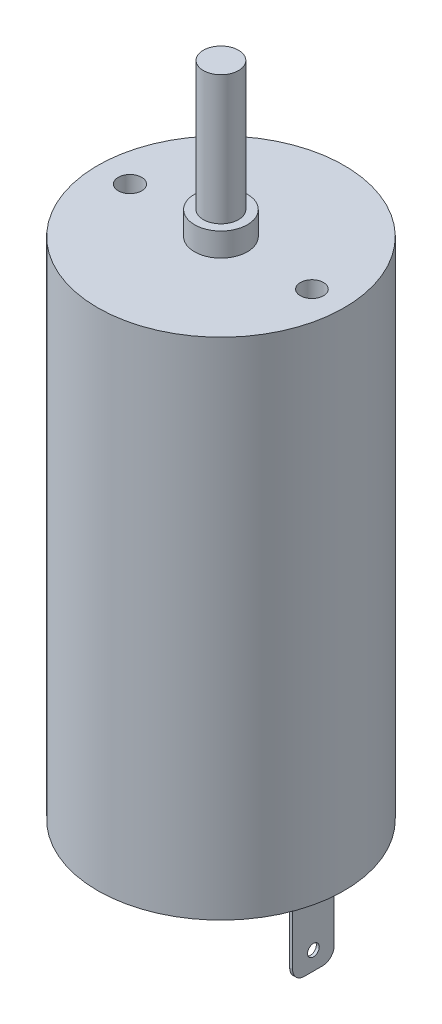
SolidWorks part; units mm, degrees
ref_plane "Front Plane" through (0, 0, 0) normal (0, 0, 1) x (1, 0, 0)
ref_plane "Top Plane" through (0, 0, 0) normal (0, 1, 0) x (1, 0, 0)
ref_plane "Right Plane" through (0, 0, 0) normal (1, 0, 0) x (0, 0, -1)
sketch "Sketch1" plane through (0, 0, 0) normal (0, 1, 0) x (1, 0, 0)
  circle A0 centre (0, 0) radius 10.5
extrude "Boss-Extrude1" add sketch "Sketch1" along normal blind 43
sketch "Sketch2" plane through (0, 43, 0) normal (0, 1, 0) x (1, 0, 0)
  circle A0 centre (0, 0) radius 1.5
extrude "Boss-Extrude2" add sketch "Sketch2" along normal blind 13
sketch "Sketch3" plane through (0, 43, 0) normal (0, 1, 0) x (1, 0, 0)
  circle A0 centre (0, 0) radius 2.25
extrude "Boss-Extrude3" add sketch "Sketch3" along normal blind 2
sketch "Sketch4" plane through (0, 43, 0) normal (0, 1, 0) x (1, 0, 0)
  line L0 (0, 0) -> (10.5, 0) construction
  line L1 (0, 0) -> (-10.5, 0) construction
  circle A0 centre (7.75, 0) radius 0.9839
  circle A1 centre (0, 0) radius 10.5 construction
  circle A2 centre (-7.75, 0) radius 1
  dimension "D1" = 2.75
  dimension "D2" = 2.75
extrude "Cut-Extrude1" cut sketch "Sketch4" against normal blind 7.5
sketch "Sketch5" plane through (0, 0, 0) normal (0, -1, 0) x (1, 0, 0)
  line L0 (0, 0) -> (10.5, 0) construction
  line L1 (10.5, 0) -> (-10.5, 0) construction
  line L3 (7.875, -2) -> (7.625, -2)
  line L4 (7.875, -2) -> (7.875, 2)
  line L5 (7.875, 2) -> (7.625, 2)
  line L6 (7.625, -2) -> (7.625, 2)
  line L7 (7.875, -2) -> (7.625, 2) construction
  line L8 (7.875, 2) -> (7.625, -2) construction
  line L9 (-7.625, -2) -> (-7.875, -2)
  line L10 (-7.625, -2) -> (-7.625, 2)
  line L11 (-7.625, 2) -> (-7.875, 2)
  line L12 (-7.875, -2) -> (-7.875, 2)
  line L13 (-7.625, -2) -> (-7.875, 2) construction
  line L14 (-7.625, 2) -> (-7.875, -2) construction
  circle A0 centre (0, 0) radius 10.5 construction
  point P6 (7.75, 0)
  point P12 (-7.75, 0)
  dimension "D1" = 0.25
  dimension "D2" = 4
  dimension "D3" = 2.75
  dimension "D4" = 0.25
  dimension "D5" = 4
  dimension "D6" = 2.75
extrude "Boss-Extrude4" add sketch "Sketch5" along normal blind 1.25
sketch "Sketch6" plane through (0, -1.25, 0) normal (0, -1, 0) x (1, 0, 0)
  line L0 (-7.625, -2) -> (-7.625, 2) construction
  line L1 (-7.625, 1.775) -> (-7.875, 1.775)
  line L2 (-7.625, 1.775) -> (-7.625, -1.775)
  line L3 (-7.625, -1.775) -> (-7.875, -1.775)
  line L4 (-7.875, 1.775) -> (-7.875, -1.775)
  line L5 (-7.875, 2) -> (-7.875, -2) construction
  line L6 (-7.625, 2) -> (-7.875, 2) construction
  line L7 (-7.875, -2) -> (-7.625, -2) construction
  dimension "D1" = 0.225
  dimension "D2" = 0.225
extrude "Boss-Extrude5" add sketch "Sketch6" along normal blind 6
fillet "Fillet1" radius 1 2 edges at (-7.75, -7.25, 1.775) (-7.75, -7.25, -1.775)
sketch "Sketch7" plane through (-7.875, 0, 0) normal (-1, 0, 0) x (0, 0, 1)
  circle A0 centre (0, -5.6963) radius 0.5
extrude "Cut-Extrude2" cut sketch "Sketch7" against normal blind 2
sketch "Sketch8" plane through (0, -1.25, 0) normal (0, -1, 0) x (1, 0, 0)
  line L0 (7.625, 2) -> (7.625, -2) construction
  line L1 (7.625, -1.77) -> (7.875, -1.77)
  line L2 (7.625, -1.77) -> (7.625, 1.77)
  line L3 (7.625, 1.77) -> (7.875, 1.77)
  line L4 (7.875, -1.77) -> (7.875, 1.77)
  line L5 (7.875, -2) -> (7.875, 2) construction
  line L6 (7.625, -2) -> (7.875, -2) construction
  line L7 (7.875, 2) -> (7.625, 2) construction
  point P8 (7.75, -1.77)
  point P11 (7.75, 1.77)
  dimension "D1" = 0.23
  dimension "D2" = 0.23
extrude "Boss-Extrude6" add sketch "Sketch8" along normal blind 6
fillet "Fillet2" radius 1 2 edges at (7.75, -7.25, 1.77) (7.75, -7.25, -1.77)
sketch "Sketch9" plane through (7.875, 0, 0) normal (1, 0, 0) x (0, 0, -1)
  line L0 (-0.77, -7.25) -> (0.77, -7.25) construction
  circle A0 centre (0, -5.7) radius 0.5
  dimension "D1" = 1.55
extrude "Cut-Extrude3" cut sketch "Sketch9" against normal blind 3
